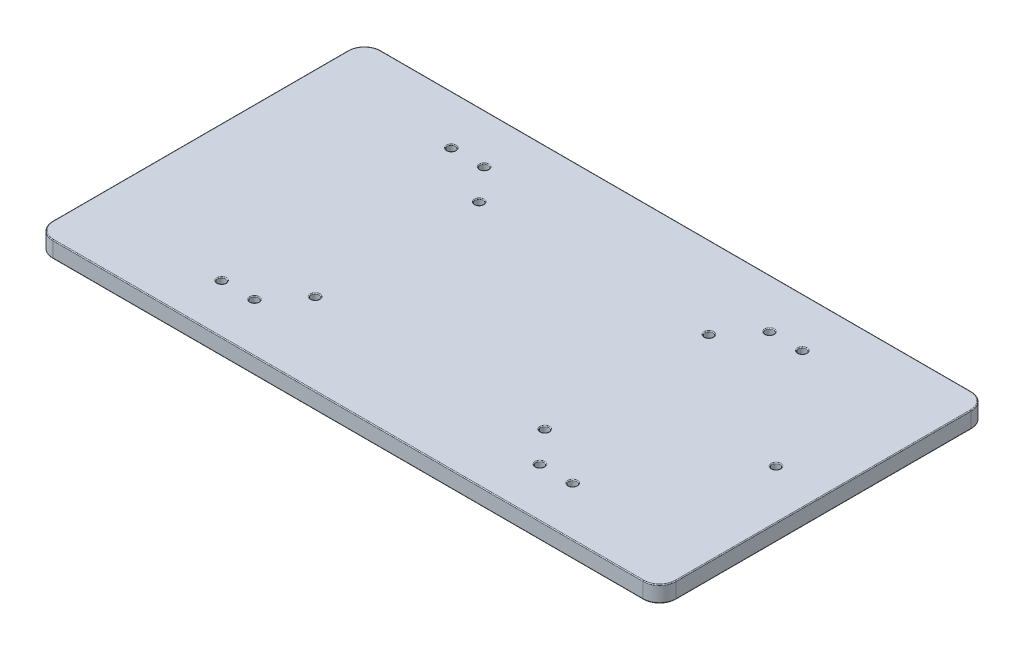
SolidWorks part; units mm, degrees
ref_plane "Front Plane" through (0, 0, 0) normal (0, 0, 1) x (1, 0, 0)
ref_plane "Top Plane" through (0, 0, 0) normal (0, 1, 0) x (1, 0, 0)
ref_plane "Right Plane" through (0, 0, 0) normal (1, 0, 0) x (0, 0, -1)
sketch "Sketch1" plane through (0, 0, 0) normal (0, 1, 0) x (1, 0, 0)
  line L0 (80, 50) -> (80, -49.0553) construction
  line L1 (-95, 50) -> (95, 50)
  line L2 (-95, 50) -> (-95, -50)
  line L3 (-95, -50) -> (95, -50)
  line L4 (95, 50) -> (95, -50)
  line L5 (-95, 50) -> (95, -50) construction
  line L6 (-95, -50) -> (95, 50) construction
  line L7 (-35, 25) -> (35, 25)
  line L8 (-35, 25) -> (-35, -25)
  line L9 (-35, -25) -> (35, -25)
  line L10 (35, 25) -> (35, -25)
  line L11 (-35, 25) -> (35, -25) construction
  line L12 (-35, -25) -> (35, 25) construction
  line L13 (0, 0) -> (20.7905, 0) construction
  line L14 (0, 0) -> (0, 17.1837) construction
  circle A0 centre (-35, 25) radius 1.25
  circle A1 centre (35, 25) radius 1.25
  circle A2 centre (35, -25) radius 1.25
  circle A3 centre (-35, -25) radius 1.25
  circle A4 centre (80, 0.4724) radius 1.25
  circle A5 centre (-53.5, -35) radius 1.25
  circle A6 centre (-43.5, -35) radius 1.25
  circle A7 centre (-43.5, 35) radius 1.25
  circle A8 centre (-53.5, 35) radius 1.25
  circle A9 centre (43.5, -35) radius 1.25
  circle A10 centre (53.5, -35) radius 1.25
  circle A11 centre (43.5, 35) radius 1.25
  circle A12 centre (53.5, 35) radius 1.25
  point P0 (0, 0)
  point P6 (0, 0)
  dimension "D5" = 2.5
  dimension "D7" = 2.5
  dimension "D8" = 2.5
  dimension "D1" = 190
  dimension "D2" = 100
  dimension "D3" = 70
  dimension "D4" = 50
  dimension "D6" = 15
  dimension "D9" = 10
  dimension "D10" = 43.5
  dimension "D11" = 15
  dimension "D12" = 15
extrude "Boss-Extrude1" add sketch "Sketch1" along normal blind 5 contours L4 L1 L2 L3 A12 A11 A9 A7 A6 A5 A4 A3 L8 A0 L7 A1 L10 A2 L9 A8 A10 | A3 L9 A2 L10 A1 L7 A0 L8
fillet "Fillet1" radius 5 4 edges at (-95, 2.5, 50) (-95, 2.5, -50) (95, 2.5, -50) (95, 2.5, 50)
fillet "Fillet2" radius 0.25 42 edges at (-35, 5, 26.25) (-35, 0, 26.25) (35, 5, -23.75) (35, 0, -23.75) (35, 5, 26.25) (35, 0, 26.25) (53.5, 5, -33.75) (53.5, 0, -33.75) (43.5, 5, -33.75) (43.5, 0, -33.75) (43.5, 5, 36.25) (43.5, 0, 36.25) (-43.5, 5, -33.75) (-43.5, 0, -33.75) (-43.5, 5, 36.25) (-43.5, 0, 36.25) (-53.5, 5, 36.25) (-53.5, 0, 36.25) (80, 5, 0.7776) (80, 0, 0.7776) (-35, 5, -23.75) (-35, 0, -23.75) (95, 0, 0) (95, 5, 0) (0, 0, -50) (0, 5, -50) (-95, 0, 0) (-95, 5, 0) (0, 5, 50) (0, 0, 50) (-53.5, 5, -33.75) (-53.5, 0, -33.75) (53.5, 5, 36.25) (53.5, 0, 36.25) (93.5355, 5, 48.5355) (93.5355, 0, 48.5355) (93.5355, 5, -48.5355) (93.5355, 0, -48.5355) (-93.5355, 5, -48.5355) (-93.5355, 0, -48.5355) (-93.5355, 5, 48.5355) (-93.5355, 0, 48.5355)
